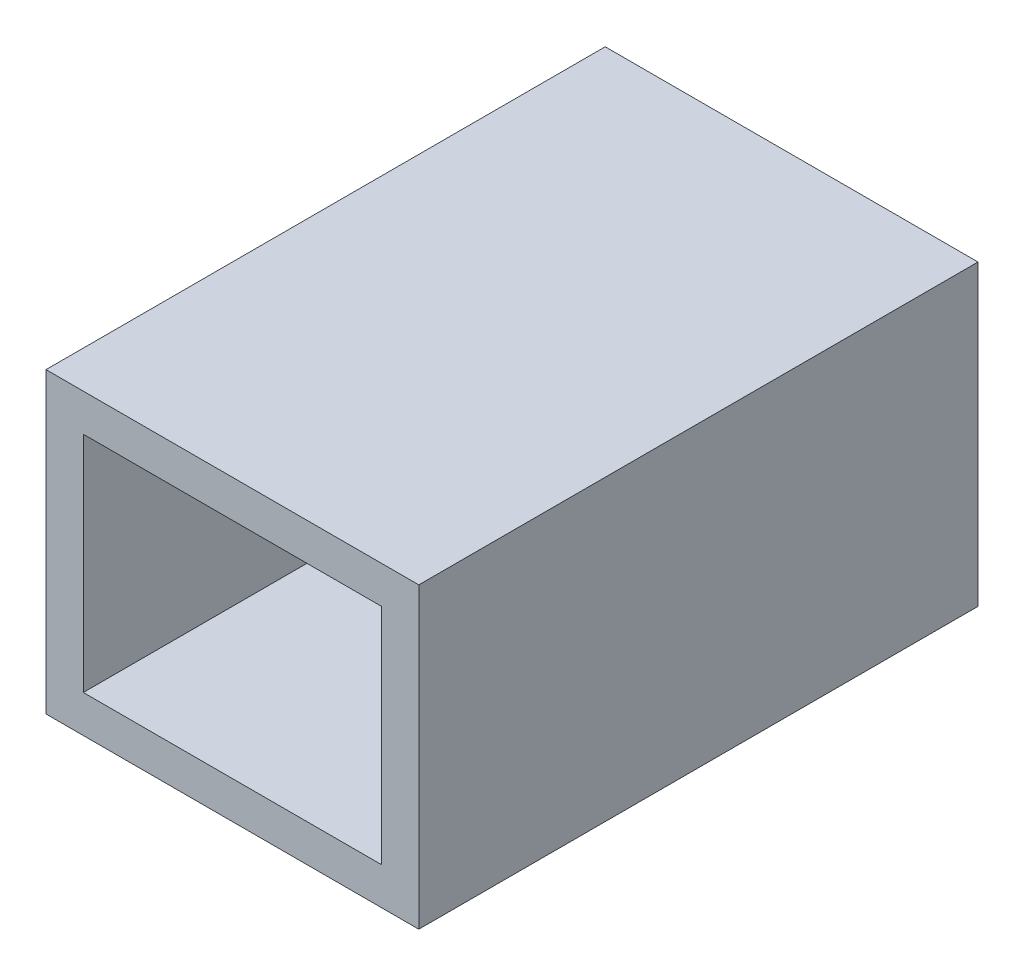
SolidWorks part; units mm, degrees
ref_plane "Ön Düzlem" through (0, 0, 0) normal (0, 0, 1) x (1, 0, 0)
ref_plane "Üst Düzlem" through (0, 0, 0) normal (0, 1, 0) x (1, 0, 0)
ref_plane "Sağ Düzlem" through (0, 0, 0) normal (1, 0, 0) x (0, 0, -1)
sketch "Sketch1" plane through (0, 0, 0) normal (0, 0, 1) x (1, 0, 0)
  line L1 (-40, -30) -> (40, -30)
  line L2 (-40, -30) -> (-40, 30)
  line L3 (-40, 30) -> (40, 30)
  line L4 (40, -30) -> (40, 30)
  line L5 (-40, -30) -> (40, 30) construction
  line L6 (-40, 30) -> (40, -30) construction
  line L7 (-50, -40) -> (50, -40)
  line L8 (-50, -40) -> (-50, 40)
  line L9 (-50, 40) -> (50, 40)
  line L10 (50, -40) -> (50, 40)
  line L11 (-50, -40) -> (50, 40) construction
  line L12 (-50, 40) -> (50, -40) construction
  point P0 (0, 0)
  point P6 (0, 0)
  dimension "D1" = 100
  dimension "D2" = 80
  dimension "D3" = 80
  dimension "D4" = 60
extrude "Boss-Extrude1" add sketch "Sketch1" along normal blind 150
